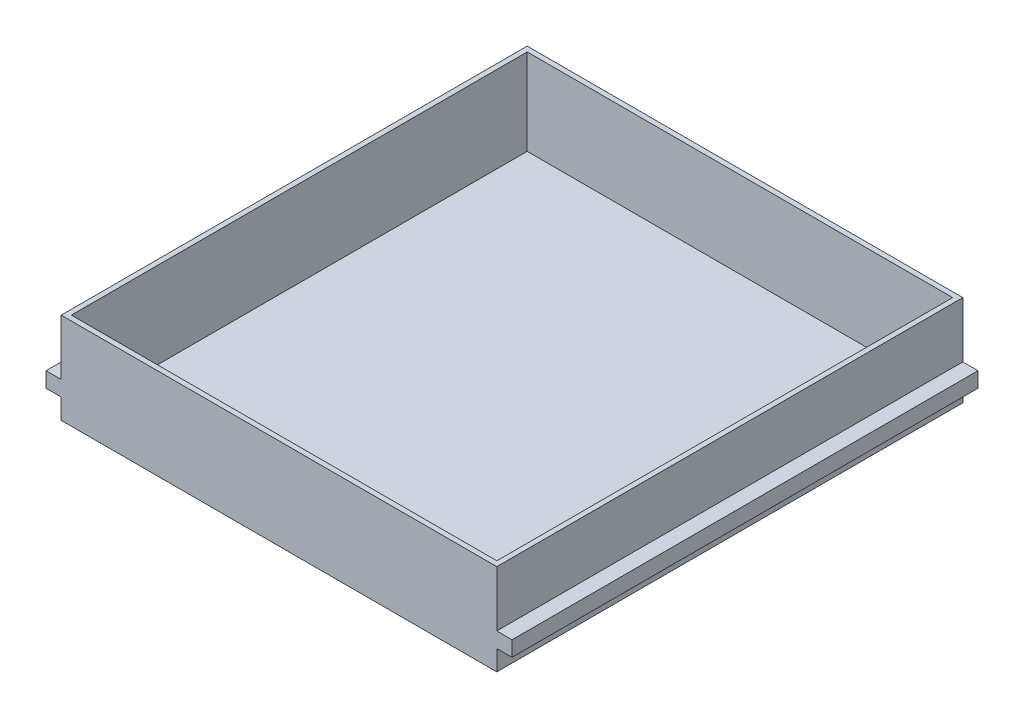
SolidWorks part; units mm, degrees
ref_plane "Front Plane" through (0, 0, 0) normal (0, 0, 1) x (1, 0, 0)
ref_plane "Top Plane" through (0, 0, 0) normal (0, 1, 0) x (1, 0, 0)
ref_plane "Right Plane" through (0, 0, 0) normal (1, 0, 0) x (0, 0, -1)
sketch "Sketch1" plane through (0, 0, 0) normal (0, 1, 0) x (1, 0, 0)
  line L1 (-546.1, -584.2) -> (546.1, -584.2)
  line L2 (-546.1, -584.2) -> (-546.1, 584.2)
  line L3 (-546.1, 584.2) -> (546.1, 584.2)
  line L4 (546.1, -584.2) -> (546.1, 584.2)
  line L5 (-546.1, -584.2) -> (546.1, 584.2) construction
  line L6 (-546.1, 584.2) -> (546.1, -584.2) construction
  point P0 (0, 0)
  dimension "D1" = 1092.2
  dimension "D2" = 1168.4
extrude "Boss-Extrude1" add sketch "Sketch1" along normal blind 12.7
sketch "Sketch2" plane through (0, 12.7, 0) normal (0, 1, 0) x (1, 0, 0)
  line L4 (-546.1, 584.2) -> (-546.1, -584.2) construction
  line L5 (-546.1, 584.2) -> (-546.1, -584.2)
  line L8 (533.4, -571.5) -> (533.4, 571.5)
  line L9 (533.4, 571.5) -> (-533.4, 571.5)
  line L10 (-533.4, 571.5) -> (-533.4, -571.5)
  line L11 (-533.4, -571.5) -> (533.4, -571.5)
  line L12 (533.4, -571.5) -> (533.4, 571.5)
  line L13 (533.4, 571.5) -> (-533.4, 571.5)
  line L14 (-533.4, 571.5) -> (-533.4, -571.5)
  line L15 (-533.4, -571.5) -> (533.4, -571.5)
  line M5 (546.1, -584.2) -> (546.1, 584.2)
  line M6 (546.1, 584.2) -> (-546.1, 584.2)
  line M7 (-546.1, 584.2) -> (-546.1, -584.2)
  line M8 (-546.1, -584.2) -> (546.1, -584.2)
  dimension "D1" = 12.7
extrude "Boss-Extrude2" add sketch "Sketch2" along normal blind 215.9 contours L15 L14 L13 L12 M8 M5 M6 M7
sketch "Sketch3" plane through (0, 0, -584.2) normal (0, 0, -1) x (-1, 0, 0)
  line L0 (546.1, 228.6) -> (546.1, 0) construction
  line L1 (546.1, 50.8) -> (584.2, 50.8)
  line L2 (546.1, 50.8) -> (546.1, 88.9)
  line L3 (546.1, 88.9) -> (584.2, 88.9)
  line L4 (584.2, 50.8) -> (584.2, 88.9)
  line L5 (-546.1, 228.6) -> (-546.1, 0) construction
  line L6 (-546.1, 50.8) -> (-584.2, 50.8)
  line L7 (-546.1, 50.8) -> (-546.1, 88.9)
  line L8 (-546.1, 88.9) -> (-584.2, 88.9)
  line L9 (-584.2, 50.8) -> (-584.2, 88.9)
  line L10 (-546.1, 0) -> (546.1, 0) construction
  dimension "D1" = 38.1
  dimension "D2" = 38.1
  dimension "D3" = 38.1
  dimension "D4" = 38.1
  dimension "D5" = 50.8
  dimension "D6" = 50.8
extrude "Boss-Extrude3" add sketch "Sketch3" against normal up to surface (1168.4 mm away) up to face at (0, 114.3, 584.2)
